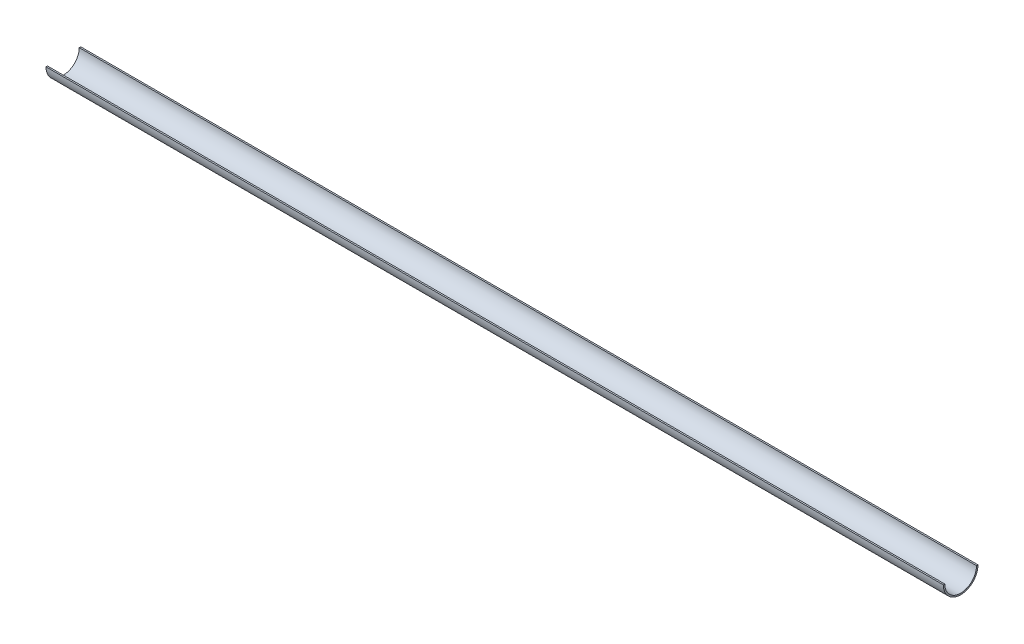
SolidWorks part; units mm, degrees
ref_plane "Спереди" through (0, 0, 0) normal (0, 0, 1) x (1, 0, 0)
ref_plane "Сверху" through (0, 0, 0) normal (0, 1, 0) x (1, 0, 0)
ref_plane "Справа" through (0, 0, 0) normal (1, 0, 0) x (0, 0, -1)
sketch "Эскиз1" plane through (0, 0, 0) normal (1, 0, 0) x (0, 0, -1)
  line L0 (119.2534, 0) -> (109.1865, 0)
  line L1 (-109.1865, 0) -> (-119.2534, 0)
  arc A0 (-119.2534, 0) -> (119.2534, 0) centre (0, 0) ccw
  arc A1 (-109.1865, 0) -> (109.1865, 0) centre (0, 0) ccw
extrude "Бобышка-Вытянуть1" add sketch "Эскиз1" along normal blind 6170
